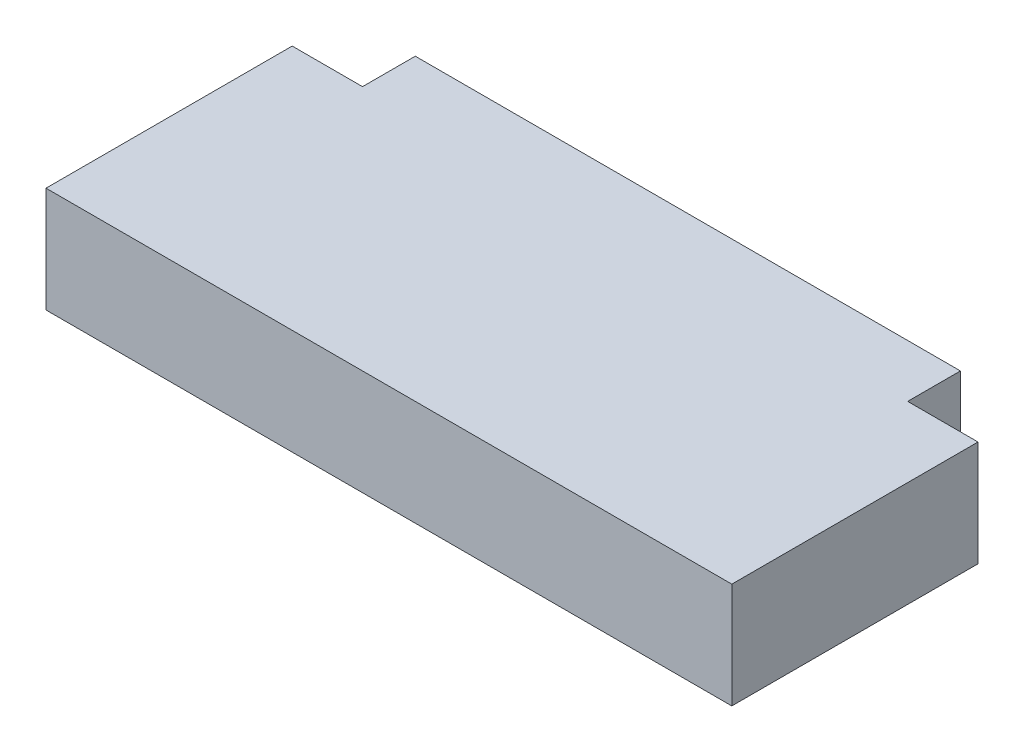
SolidWorks part; units mm, degrees
ref_plane "Front Plane" through (0, 0, 0) normal (0, 0, 1) x (1, 0, 0)
ref_plane "Top Plane" through (0, 0, 0) normal (0, 1, 0) x (1, 0, 0)
ref_plane "Right Plane" through (0, 0, 0) normal (1, 0, 0) x (0, 0, -1)
sketch "Sketch1" plane through (0, 0, 0) normal (0, 1, 0) x (1, 0, 0)
  line L1 (-9, 2.4408) -> (10.5, 2.4408)
  line L2 (-9, 2.4408) -> (-9, -6.0592)
  line L3 (-9, -6.0592) -> (10.5, -6.0592)
  line L4 (10.5, 2.4408) -> (10.5, -6.0592)
  dimension "D1" = 19.5
  dimension "D2" = 8.5
extrude "Boss-Extrude1" add sketch "Sketch1" along normal blind 3
sketch "Sketch2" plane through (0, 3, 0) normal (0, 1, 0) x (1, 0, 0)
  line L0 (-9, 2.4408) -> (-9, -6.0592) construction
  line L1 (-9, 0.9408) -> (-7, 0.9408)
  line L2 (-9, 0.9408) -> (-9, 2.4408)
  line L3 (-9, 2.4408) -> (-7, 2.4408)
  line L4 (-7, 0.9408) -> (-7, 2.4408)
  line L5 (10.5, 2.4408) -> (-9, 2.4408) construction
  line L6 (-9, -6.0592) -> (10.5, -6.0592) construction
  line L8 (10.5, 2.4408) -> (8.5, 2.4408)
  line L9 (10.5, 2.4408) -> (10.5, 0.9408)
  line L10 (10.5, 0.9408) -> (8.5, 0.9408)
  line L11 (8.5, 2.4408) -> (8.5, 0.9408)
  dimension "D1" = 7
  dimension "D2" = 2
extrude "Cut-Extrude1" cut sketch "Sketch2" against normal through all
